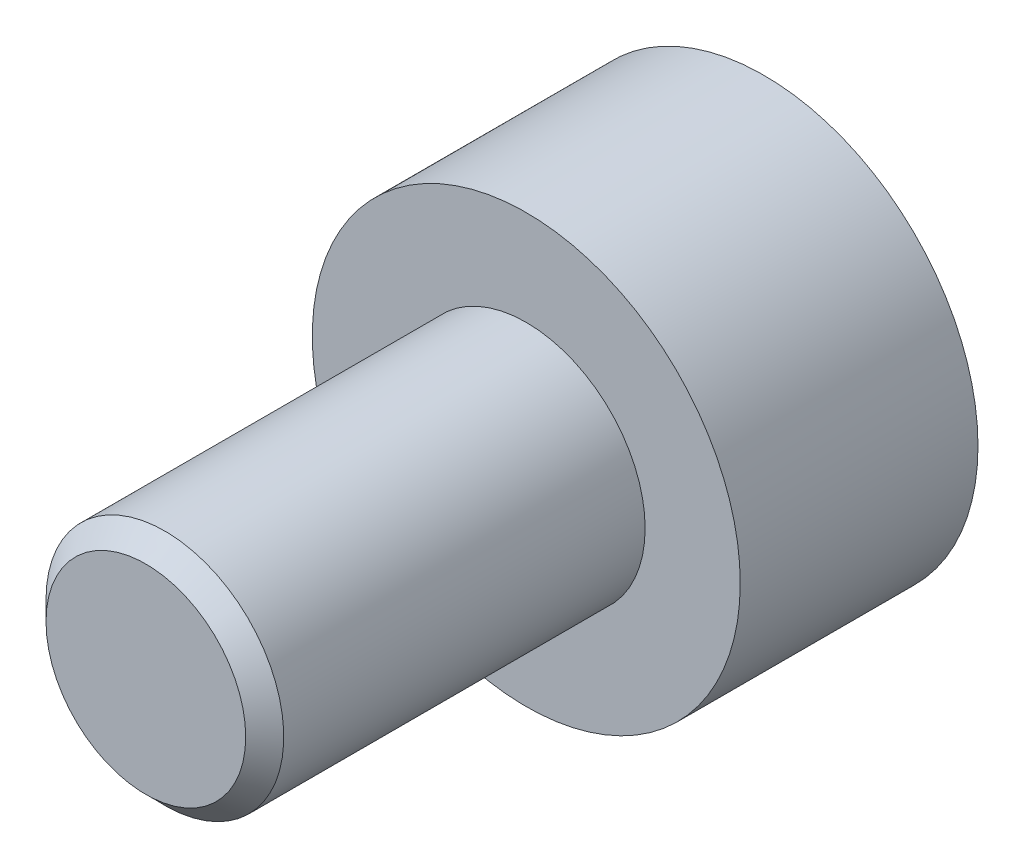
SolidWorks part; units mm, degrees
material "AISI 304"
ref_plane "前视基准面" through (0, 0, 0) normal (0, 0, 1) x (1, 0, 0)
ref_plane "上视基准面" through (0, 0, 0) normal (0, 1, 0) x (1, 0, 0)
ref_plane "右视基准面" through (0, 0, 0) normal (1, 0, 0) x (0, 0, -1)
sketch "草图1" plane through (0, 0, 0) normal (0, 0, 1) x (1, 0, 0)
  circle A0 centre (0, 0) radius 2.25
  dimension "D1" = 4.5
extrude "凸台-拉伸1" add sketch "草图1" along normal blind 2.5
sketch "草图2" plane through (0, 0, 2.5) normal (0, 0, 1) x (1, 0, 0)
  circle A0 centre (0, 0) radius 1.25
  dimension "D1" = 2.5
extrude "凸台-拉伸2" add sketch "草图2" along normal blind 4
chamfer "倒角1" distance 0.2 angle 45 1 edges at (1.25, 0, 6.5)
sketch "草图3" plane through (0, 0, 0) normal (0, 0, -1) x (-1, 0, 0)
  line L0 (0, 1.1778) -> (-1.02, 0.5889)
  line L1 (-1.02, 0.5889) -> (-1.02, -0.5889)
  line L2 (-1.02, -0.5889) -> (0, -1.1778)
  line L3 (0, -1.1778) -> (1.02, -0.5889)
  line L4 (1.02, -0.5889) -> (1.02, 0.5889)
  line L5 (1.02, 0.5889) -> (0, 1.1778)
  dimension "D1" = 2.04
extrude "切除-拉伸1" cut sketch "草图3" against normal blind 1.1
